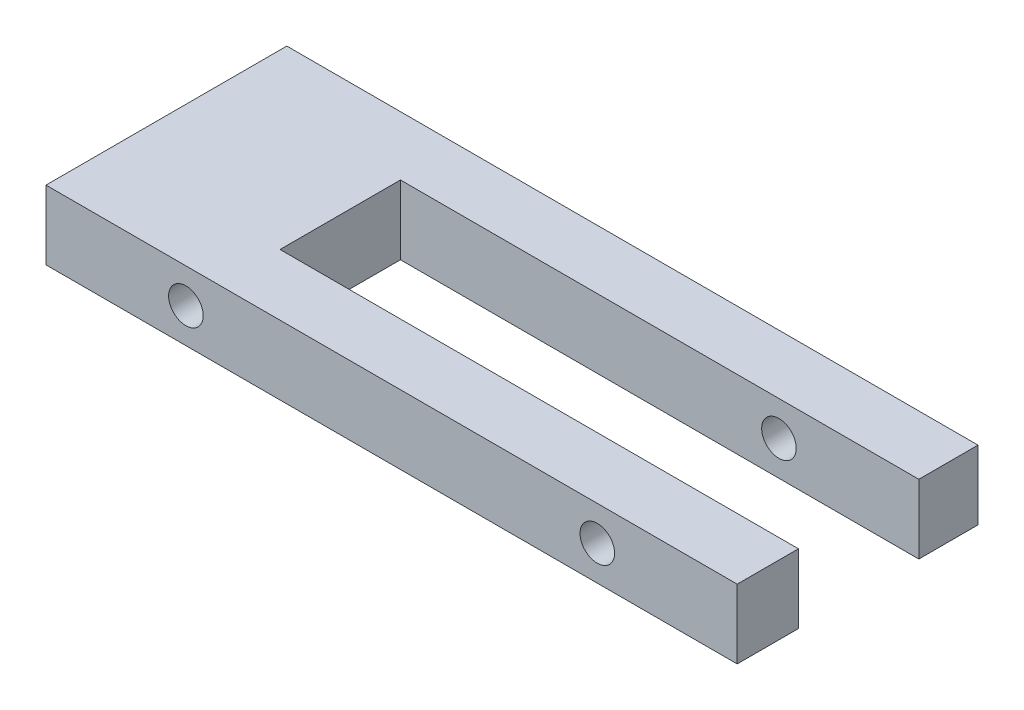
SolidWorks part; units mm, degrees
ref_plane "Front Plane" through (0, 0, 0) normal (0, 0, 1) x (1, 0, 0)
ref_plane "Top Plane" through (0, 0, 0) normal (0, 1, 0) x (1, 0, 0)
ref_plane "Right Plane" through (0, 0, 0) normal (1, 0, 0) x (0, 0, -1)
ref_plane "Plane1" through (0, 0, 0) normal (0, -1, 0) x (-1, 0, 0)
sketch "Base Boundaries" plane through (0, 0, 0) normal (0, -1, 0) x (-1, 0, 0)
  line L0 (0, 0) -> (0, 246.9925) construction
  line L1 (0, 0) -> (0, -253.0075) construction
  line L2 (0, 0) -> (-500, 0) construction
  line L3 (0, 0) -> (500, 0) construction
  line L4 (-500, 0) -> (-500, 246.9925) construction
  line L5 (-500, 246.9925) -> (0, 246.9925) construction
  line L6 (0, 246.9925) -> (500, 246.9925) construction
  line L7 (500, 246.9925) -> (500, 0) construction
  line L8 (500, 0) -> (500, -253.0075) construction
  line L9 (500, -253.0075) -> (0, -253.0075) construction
  line L10 (0, -253.0075) -> (-500, -253.0075) construction
  line L11 (-500, -253.0075) -> (-500, 0) construction
  line L12 (-500, 246.9925) -> (-500, 196.1925) construction
  line L13 (-500, 196.1925) -> (500, 196.1925) construction
  line L14 (500, 196.1925) -> (500, 246.9925) construction
  line L15 (-500, -253.0075) -> (-500, -202.2075) construction
  line L16 (-500, -202.2075) -> (0, -202.2075) construction
  line L17 (0, -202.2075) -> (500, -202.2075) construction
  line L18 (500, -202.2075) -> (500, -253.0075) construction
  line L19 (-500, 246.9925) -> (0, 196.1925) construction
  line L20 (0, 196.1925) -> (500, 246.9925) construction
  line L21 (0, 246.9925) -> (500, 196.1925) construction
  line L22 (0, 246.9925) -> (-500, 196.1925) construction
  line L23 (-500, -253.0075) -> (0, -202.2075) construction
  line L24 (0, -202.2075) -> (500, -253.0075) construction
  line L25 (500, -202.2075) -> (0, -253.0075) construction
  line L26 (0, -253.0075) -> (-500, -202.2075) construction
  line L27 (-500, 196.1925) -> (-500, 171.1925) construction
  line L28 (-500, 171.1925) -> (500, 171.1925) construction
  line L29 (-500, -202.2075) -> (-500, -177.2075) construction
  line L30 (-500, -177.2075) -> (500, -177.2075) construction
  line L31 (500, -177.2075) -> (500, -202.2075) construction
  line L32 (-500, 171.1925) -> (500, 196.1925) construction
  line L33 (500, 171.1925) -> (-500, 196.1925) construction
  line L34 (-500, -202.2075) -> (500, -177.2075) construction
  line L35 (500, -202.2075) -> (-500, -177.2075) construction
  dimension "D1" = 500
  dimension "D2" = 1000
  dimension "D3" = 50.8
  dimension "D4" = 50.8
  dimension "D5" = 25
  dimension "D6" = 25
sketch "Wheel Lines" plane through (0, 0, 0) normal (0, -1, 0) x (-1, 0, 0)
  line L0 (-500, 246.9925) -> (-500, 196.1925) construction
  line L1 (-500, 196.1925) -> (-95.2, 196.1925) construction
  line L2 (-500, 196.1925) -> (500, 196.1925) construction
  line L3 (-95.2, 196.1925) -> (-95.2, 246.9925) construction
  line L4 (-500, 246.9925) -> (0, 246.9925) construction
  line L5 (-95.2, 246.9925) -> (-500, 246.9925) construction
  line L6 (-500, -202.2075) -> (-500, -253.0075) construction
  line L7 (-500, -253.0075) -> (-95.2, -202.2075) construction
  line L8 (-500, -202.2075) -> (0, -202.2075) construction
  line L9 (-95.2, -202.2075) -> (-95.2, -253.0075) construction
  line L10 (0, -253.0075) -> (-500, -253.0075) construction
  line L11 (-95.2, -253.0075) -> (-500, -202.2075) construction
  line L12 (500, 246.9925) -> (95.2, 246.9925) construction
  line L13 (0, 246.9925) -> (500, 246.9925) construction
  line L14 (95.2, 246.9925) -> (500, 196.1925) construction
  line L15 (500, 196.1925) -> (95.2, 196.1925) construction
  line L16 (95.2, 196.1925) -> (95.2, 246.9925) construction
  line L17 (500, -202.2075) -> (95.2, -202.2075) construction
  line L18 (0, -202.2075) -> (500, -202.2075) construction
  line L19 (95.2, -202.2075) -> (95.2, -253.0075) construction
  line L20 (500, -253.0075) -> (0, -253.0075) construction
  line L21 (95.2, -253.0075) -> (500, -202.2075) construction
  line L22 (500, -202.2075) -> (500, -253.0075) construction
  line L23 (500, -253.0075) -> (95.2, -202.2075) construction
  line L24 (-95.2, 246.9925) -> (-500, 196.1925) construction
  line L25 (-500, 246.9925) -> (-95.2, 196.1925) construction
  line L26 (95.2, 196.1925) -> (500, 246.9925) construction
  line L27 (297.6, 221.5925) -> (297.6, -227.2075) construction
  line L28 (-297.6, 221.5925) -> (-297.6, -227.2075) construction
  dimension "D1" = 404.8
  dimension "D2" = 404.8
  dimension "D3" = 404.8
  dimension "D4" = 404.8
  dimension "D5" = 595.2
ref_plane "Plane2" through (0, 0, 0) normal (0, -1, 0) x (-1, 0, 0)
sketch "Sketch5" plane through (0, 0, 0) normal (0, -1, 0) x (-1, 0, 0)
  line L0 (-500, 171.1925) -> (500, 171.1925)
  line L1 (500, 171.1925) -> (500, -177.2075)
  line L2 (500, -177.2075) -> (-500, -177.2075)
  line L3 (-500, 0) -> (0, -177.2075) construction
  line L4 (0, 0) -> (-500, -177.2075) construction
  line L5 (-250, -88.6038) -> (-500, -88.6038) construction
  line L6 (-500, -253.0075) -> (-500, 0) construction
  line L7 (-500, -88.6038) -> (500, -88.6038) construction
  line L8 (-500, 171.1925) -> (0, 0) construction
  line L9 (0, 171.1925) -> (-500, 0) construction
  line L10 (-250, 85.5962) -> (-500, 85.5962) construction
  line L11 (-500, 0) -> (-500, 246.9925) construction
  line L12 (-250, 85.5962) -> (500, 85.5962) construction
  line L13 (-500, 171.1925) -> (-500, 85.5962)
  line L14 (0, 171.1925) -> (500, 85.5962) construction
  line L15 (500, 171.1925) -> (0, 85.5962) construction
  line L16 (0, 0) -> (0, 246.9925) construction
  line L17 (250, 128.3944) -> (250, -88.6038) construction
  line L18 (-500, 85.5962) -> (250, 85.5962) construction
  line L19 (250, 85.5962) -> (250, -88.6038) construction
  line L20 (-500, 85.5962) -> (250, 85.5962)
  line L21 (250, 85.5962) -> (250, -88.6038)
  line L22 (250, -88.6038) -> (-500, -88.6038)
  line L23 (-500, -88.6038) -> (-500, -177.2075)
extrude "Boss-Extrude1" add sketch "Sketch5" along normal blind 100
sketch "Sketch6" plane through (0, -100, 0) normal (0, -1, 0) x (-1, 0, 0)
  line L0 (-297.6, 171.1925) -> (-297.6, 85.5962) construction
  line L1 (-500, 171.1925) -> (500, 171.1925) construction
  line L2 (-297.6, 221.5925) -> (-297.6, -227.2075) construction
  line L3 (-500, 85.5962) -> (250, 85.5962) construction
ref_plane "Plane3" through (0, 0, -171.1925) normal (0, 0, -1) x (-1, 0, 0)
sketch "Sketch8" plane through (0, 0, -171.1925) normal (0, 0, -1) x (-1, 0, 0)
  line L0 (-297.6, -100) -> (-297.6, 0) construction
  line L1 (-500, -50) -> (500, -50) construction
  line L3 (-500, -100) -> (-500, 0) construction
  line L4 (500, -100) -> (500, 0) construction
  line L5 (0, -50) -> (0, 0) construction
  line L6 (0, -50) -> (0, -100) construction
  line L7 (500, -100) -> (-500, -100) construction
  circle A0 centre (-297.6, -50) radius 25
  circle A1 centre (297.6, -50) radius 25
  dimension "D1" = 50
extrude "Cut-Extrude1" cut sketch "Sketch8" against normal up to surface (348.4 mm away) contours A0 | A1 up to face at (0, -50, 177.2075)
